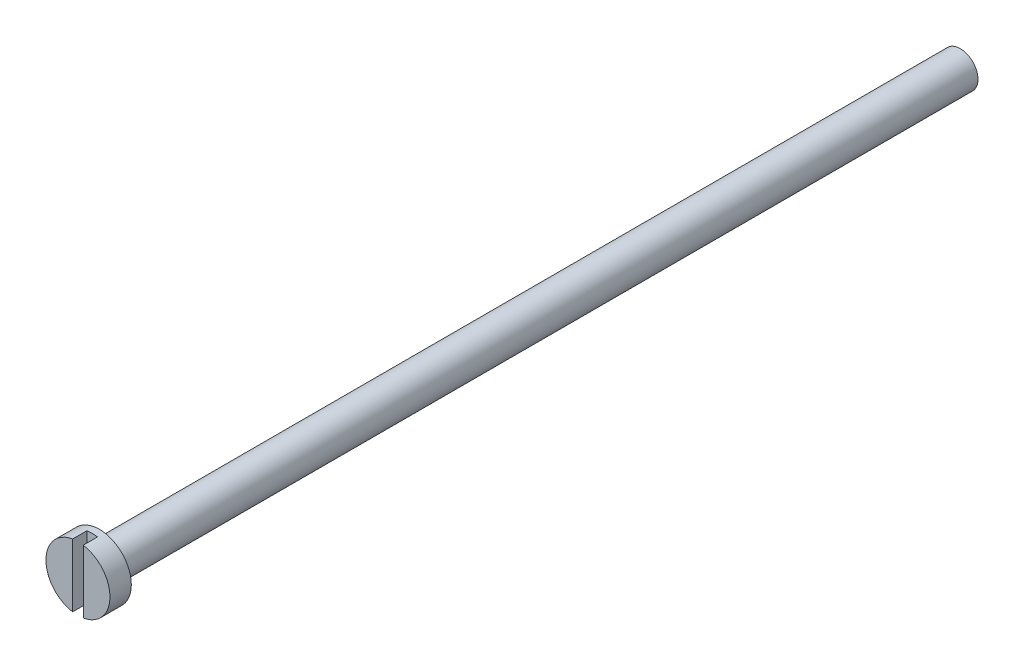
SolidWorks part; units mm, degrees
ref_plane "前视基准面" through (0, 0, 0) normal (0, 0, 1) x (1, 0, 0)
ref_plane "上视基准面" through (0, 0, 0) normal (0, 1, 0) x (1, 0, 0)
ref_plane "右视基准面" through (0, 0, 0) normal (1, 0, 0) x (0, 0, -1)
sketch "草图1" plane through (0, 0, 0) normal (0, 0, 1) x (1, 0, 0)
  circle A0 centre (0, 0) radius 2.5
  dimension "D1" = 5
extrude "凸台-拉伸1" add sketch "草图1" along normal blind 121
cosmetic thread "装饰螺纹线2" parameters "D1"=10, "D2"=4.134
cosmetic thread "装饰螺纹线3" parameters "D1"=7, "D2"=4
sketch "草图2" plane through (0, 0, 121) normal (0, 0, 1) x (1, 0, 0)
  circle A0 centre (0, 0) radius 4.5
  dimension "D1" = 9
extrude "凸台-拉伸2" add sketch "草图2" along normal blind 3
sketch "草图4" plane through (0, 0, 124) normal (0, 0, 1) x (1, 0, 0)
  line L1 (-0.75, 5.4684) -> (0.75, 5.4684)
  line L2 (-0.75, 5.4684) -> (-0.75, -5.4684)
  line L3 (-0.75, -5.4684) -> (0.75, -5.4684)
  line L4 (0.75, 5.4684) -> (0.75, -5.4684)
  line L5 (-0.75, 5.4684) -> (0.75, -5.4684) construction
  line L6 (-0.75, -5.4684) -> (0.75, 5.4684) construction
  point P0 (0, 0)
  dimension "D1" = 1.5
extrude "切除-拉伸1" cut sketch "草图4" against normal blind 2
